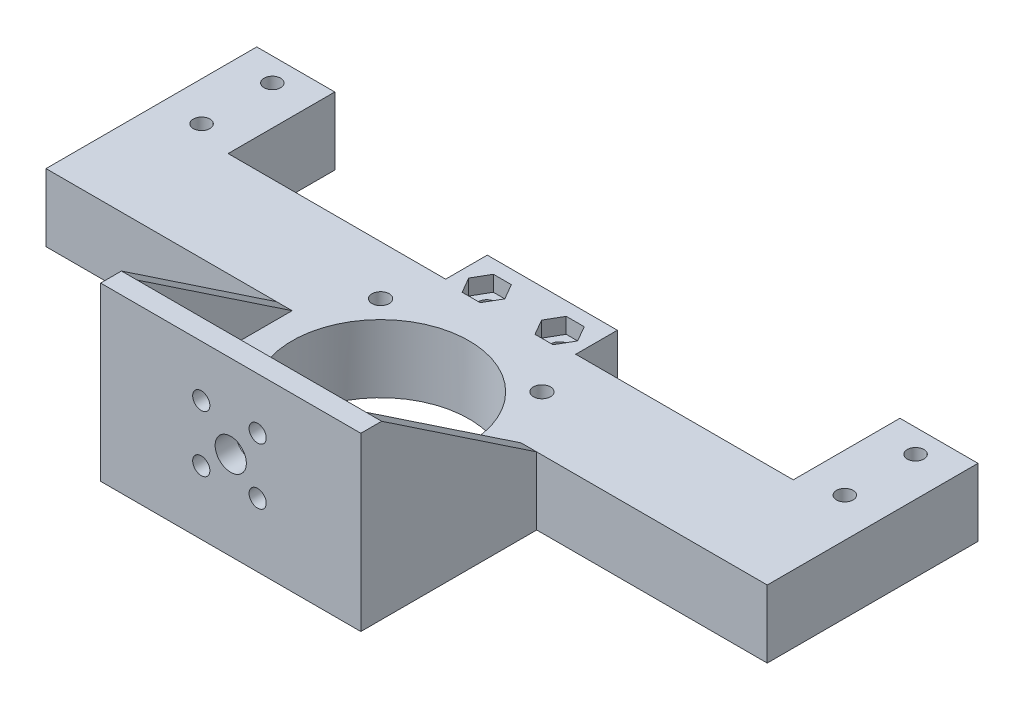
SolidWorks part; units mm, degrees
ref_plane "前视基准面" through (0, 0, 0) normal (0, 0, 1) x (1, 0, 0)
ref_plane "上视基准面" through (0, 0, 0) normal (0, 1, 0) x (1, 0, 0)
ref_plane "右视基准面" through (0, 0, 0) normal (1, 0, 0) x (0, 0, -1)
sketch "草图2" plane through (0, 0, 0) normal (0, 1, 0) x (1, 0, 0)
  line L15 (-44.3, 33.8) -> (-44.3, 74.3)
  line L16 (-44.3, 74.3) -> (-29.3, 74.3)
  line L17 (-29.3, 74.3) -> (-29.3, 53.8)
  line L18 (-29.3, 53.8) -> (12.5, 53.8)
  line L19 (12.5, 53.8) -> (12.5, 61.8)
  line L20 (12.5, 61.8) -> (37.5, 61.8)
  line L21 (37.5, 61.8) -> (37.5, 53.8)
  line L22 (37.5, 53.8) -> (79.3, 53.8)
  line L23 (79.3, 53.8) -> (79.3, 74.3)
  line L24 (79.3, 74.3) -> (94.3, 74.3)
  line L25 (94.3, 74.3) -> (94.3, 33.8)
  line L27 (-44.3, 33.8) -> (0, 33.8)
  line L28 (0, 33.8) -> (0, 0)
  line L29 (0, 0) -> (50, 0)
  line L30 (50, 0) -> (50, 33.8)
  line L31 (50, 33.8) -> (94.3, 33.8)
  line L32 (25, -43.9837) -> (25, 32.7782) construction
  line L33 (86.8, 69.8) -> (86.8, -14.8283) construction
  line L34 (-36.8, 69.8) -> (-36.8, -33.736) construction
  line L35 (25, 66.1921) -> (25, -26.5769) construction
  circle A0 centre (-36.8, 69.8) radius 1.6
  circle A1 centre (-36.8, 56.2) radius 1.6
  circle A2 centre (86.8, 69.8) radius 1.6
  circle A3 centre (86.8, 56.2) radius 1.6
  circle A6 centre (18, 56.2) radius 1.6
  circle A7 centre (32, 56.2) radius 1.6
  circle A10 centre (25, 28.8) radius 17
  circle A11 centre (40.5, 44.3) radius 1.65
  circle A12 centre (40.5, 13.3) radius 1.65
  circle A13 centre (9.5, 13.3) radius 1.65
  circle A14 centre (9.5, 44.3) radius 1.65
  point P0 (-36.8, 56.2)
  point P1 (86.8, 56.2)
  point P2 (86.8, 69.8)
  point P3 (-36.8, 69.8)
  point P4 (32, 56.2)
  point P6 (18, 56.2)
  point P10 (86.8, 43.9236)
  point P11 (0, 0)
  point P39 (0, 0)
  point P50 (25, 28.8)
  dimension "D2" = 123.6
  dimension "D20" = 3.2
  dimension "D22" = 34
  dimension "D7" = 28.8
  dimension "D10" = 50
  dimension "D11" = 25
  dimension "D14" = 3.3
  dimension "D17" = 31
  dimension "D3" = 13.6
  dimension "D4" = 14
  dimension "D5" = 54.8
  dimension "D8" = 8
  dimension "D9" = 25
  dimension "D12" = 15
  dimension "D13" = 15
  dimension "D15" = 20
  dimension "D16" = 4
  dimension "D18" = 4.5
extrude "凸台-拉伸2" add sketch "草图2" along normal blind 13
sketch "草图3" plane through (0, 13, 0) normal (0, 1, 0) x (1, 0, 0)
  line L1 (21.4641, 56.2) -> (19.7321, 59.2)
  line L2 (19.7321, 59.2) -> (16.2679, 59.2)
  line L3 (16.2679, 59.2) -> (14.5359, 56.2)
  line L4 (14.5359, 56.2) -> (16.2679, 53.2)
  line L5 (16.2679, 53.2) -> (19.7321, 53.2)
  line L6 (19.7321, 53.2) -> (21.4641, 56.2)
  line L7 (35.4641, 56.2) -> (33.7321, 59.2)
  line L8 (33.7321, 59.2) -> (30.2679, 59.2)
  line L9 (30.2679, 59.2) -> (28.5359, 56.2)
  line L10 (28.5359, 56.2) -> (30.2679, 53.2)
  line L11 (30.2679, 53.2) -> (33.7321, 53.2)
  line L12 (33.7321, 53.2) -> (35.4641, 56.2)
  circle A0 centre (18, 56.2) radius 3 construction
  circle A1 centre (32, 56.2) radius 3 construction
  dimension "D1" = 6
  dimension "D2" = 6
extrude "切除-拉伸1" cut sketch "草图3" against normal blind 3
sketch "草图6" plane through (0, 13, 0) normal (0, 1, 0) x (1, 0, 0)
  line L0 (0, 33.8) -> (0, 0)
  line L1 (0, 0) -> (50, 0)
  line L2 (0, 0) -> (50, 0) construction
  line L3 (50, 0) -> (50, 33.8)
  line L4 (50, 33.8) -> (47, 33.8)
  line L5 (47, 33.8) -> (47, 4)
  line L6 (47, 4) -> (3, 4)
  line L7 (3, 4) -> (3, 33.8)
  line L8 (3, 33.8) -> (0, 33.8)
  line L9 (25, 28.8) -> (25, -10.253) construction
  line L10 (50, 0) -> (50, 33.8) construction
  line L11 (50, 33.8) -> (94.3, 33.8) construction
  dimension "D1" = 4
  dimension "D2" = 3
  dimension "D3" = 3
extrude "凸台-拉伸3" add sketch "草图6" along normal blind 20
sketch "草图7" plane through (0, 0, 0) normal (-1, 0, 0) x (0, 0, 1)
  line L0 (-33.8, 13) -> (-4, 33)
  line L1 (-4, 33) -> (-33.8, 33)
  line L2 (-33.8, 33) -> (-33.8, 13)
  line L3 (-33.8, 33) -> (0, 33) construction
extrude "切除-拉伸2" cut sketch "草图7" against normal through all
sketch "草图8" plane through (0, 13, 0) normal (0, 1, 0) x (1, 0, 0)
  line L0 (25, 4) -> (25, 16.5176) construction
  line L1 (47, 4) -> (3, 4) construction
  line L2 (47, 4) -> (3, 4) construction
  line L3 (13, 4) -> (37, 4)
  line L4 (13, 4) -> (13, 24)
  line L5 (13, 24) -> (37, 24)
  line L6 (37, 4) -> (37, 24)
  dimension "D1" = 24
  dimension "D2" = 20
extrude "切除-拉伸3" cut sketch "草图8" against normal blind 6
sketch "草图10" plane through (0, 0, 0) normal (0, 0, 1) x (1, 0, 0)
  line L0 (25, 33) -> (25, -8.8083) construction
  line L1 (0, 33) -> (50, 33) construction
  line L2 (13, 7) -> (37, 7) construction
  circle A0 centre (25, 17) radius 3
  circle A1 centre (30.1735, 23.1021) radius 1.65
  circle A2 centre (30.1735, 12.2647) radius 1.65
  circle A3 centre (19.3361, 12.2647) radius 1.65
  circle A4 centre (19.3361, 23.1021) radius 1.65
  point P19 (24.7548, 17.6834)
  dimension "D1" = 10
  dimension "D2" = 6
  dimension "D3" = 3.3
  dimension "D4" = 8
  dimension "D5" = 4
extrude "切除-拉伸4" cut sketch "草图10" against normal blind 5
